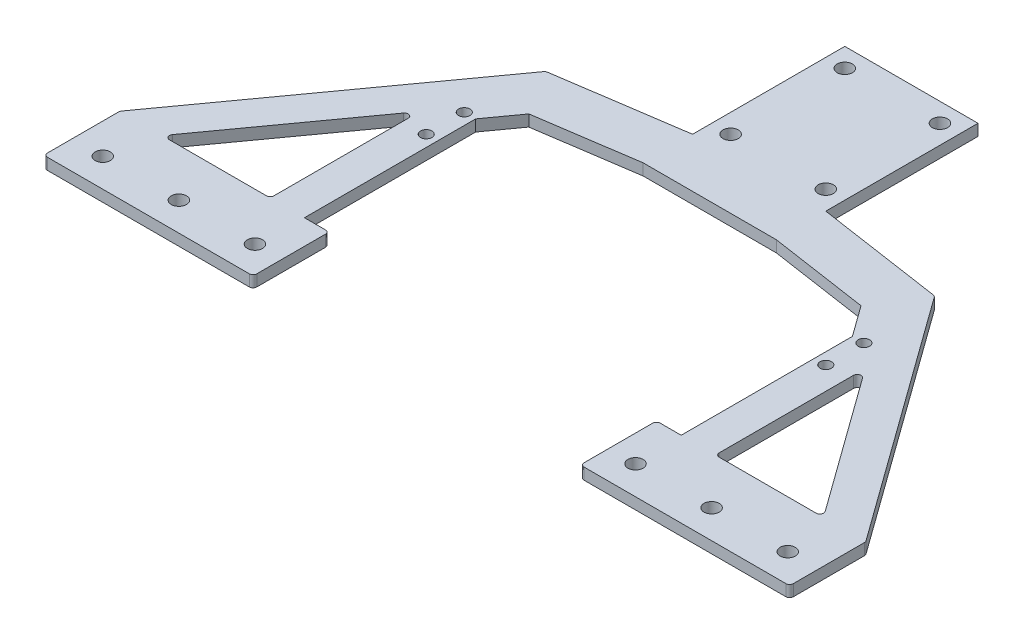
SolidWorks part; units mm, degrees
material "Thornel Mat VMA"
ref_plane "前视基准面" through (0, 0, 0) normal (0, 0, 1) x (1, 0, 0)
ref_plane "上视基准面" through (0, 0, 0) normal (0, 1, 0) x (1, 0, 0)
ref_plane "右视基准面" through (0, 0, 0) normal (1, 0, 0) x (0, 0, -1)
sketch "草图1" plane through (0, 0, 0) normal (0, 1, 0) x (1, 0, 0)
  line L0 (0, 0) -> (0, -110)
  line L1 (0, -110) -> (-62.5, -110)
  line L2 (-62.5, -110) -> (-62.5, -130)
  line L3 (-62.5, -130) -> (97.5, -130)
  line L4 (97.5, -130) -> (97.5, -110)
  line L5 (97.5, -110) -> (35, -110)
  line L6 (35, -110) -> (35, 0)
  line L7 (35, 0) -> (0, 0)
  line L9 (5, -5) -> (30, -5) construction
  line L10 (5, -5) -> (5, -35) construction
  line L11 (5, -35) -> (30, -35) construction
  line L12 (30, -5) -> (30, -35) construction
  circle A0 centre (5, -5) radius 2
  circle A1 centre (30, -5) radius 2
  circle A2 centre (5, -35) radius 2
  circle A3 centre (30, -35) radius 2
  circle A4 centre (-52.5, -122.5) radius 2
  circle A5 centre (-32.5, -122.5) radius 2
  circle A6 centre (-12.5, -122.5) radius 2
  circle A7 centre (7.5, -122.5) radius 2
  circle A8 centre (27.5, -122.5) radius 2
  circle A9 centre (47.5, -122.5) radius 2
  circle A10 centre (67.5, -122.5) radius 2
  circle A11 centre (87.5, -122.5) radius 2
  point P7 (17.5, -5)
  dimension "D10" = 4
  dimension "D11" = 7.5
  dimension "D13" = 4
  dimension "D1" = 35
  dimension "D2" = 130
  dimension "D3" = 20
  dimension "D4" = 160
  dimension "D5" = 62.5
  dimension "D6" = 5
  dimension "D7" = 5
  dimension "D8" = 5
  dimension "D9" = 30
  dimension "D12" = 10
  dimension "D15" = 10
  dimension "D14" = 8
extrude "凸台-拉伸1" add sketch "草图1" along normal blind 4
sketch "草图2" plane through (0, 4, 0) normal (0, 1, 0) x (1, 0, 0)
  line L0 (17.5, 0) -> (17.5, -130) construction
  line L1 (-35, -65) -> (70, -65) construction
  line L2 (-35, -65) -> (-35, -75) construction
  line L3 (-35, -75) -> (70, -75) construction
  line L5 (35, 0) -> (0, 0) construction
  line L6 (-62.5, -130) -> (97.5, -130) construction
  line L7 (70, -65) -> (70, -75) construction
  line L34 (0, 0) -> (0, -110) construction
  line L35 (0, -40) -> (0, -53)
  line L44 (0, -40) -> (-33.6, -45)
  line L45 (-33.6, -45) -> (-80.5, -110)
  line L46 (0, -53) -> (-26.1492, -56.8913)
  line L47 (-26.1492, -56.8913) -> (-32, -65)
  line L48 (-32, -65) -> (-32, -110)
  line L50 (-80.5, -110) -> (-80.5, -130)
  line L51 (-80.5, -130) -> (-62.5, -130)
  line L52 (-62.5, -130) -> (-62.5, -110)
  line L65 (0, -110) -> (-62.5, -110) construction
  line L66 (-32, -110) -> (-41, -110)
  line L67 (-69.4018, -110) -> (-41, -70.6372)
  line L68 (-41, -70.6372) -> (-41, -110)
  line L69 (-62.5, -110) -> (-69.4018, -110)
  line L71 (67, -65) -> (67, -110)
  line L72 (61.1492, -56.8913) -> (67, -65)
  line L73 (35, -53) -> (61.1492, -56.8913)
  line L74 (35, -40) -> (35, -53)
  line L75 (35, -40) -> (68.6, -45)
  line L76 (68.6, -45) -> (115.5, -110)
  line L77 (115.5, -110) -> (115.5, -130)
  line L78 (115.5, -130) -> (97.5, -130)
  line L79 (97.5, -130) -> (97.5, -110)
  line L80 (97.5, -110) -> (104.4018, -110)
  line L81 (104.4018, -110) -> (76, -70.6372)
  line L82 (76, -70.6372) -> (76, -110)
  line L83 (67, -110) -> (76, -110)
  line L84 (-52.5, -122.5) -> (-72.5, -122.5) construction
  circle A0 centre (-35, -65) radius 1.5
  circle A1 centre (-35, -75) radius 1.5
  circle A2 centre (70, -65) radius 1.5
  circle A3 centre (70, -75) radius 1.5
  circle A4 centre (-52.5, -122.5) radius 2 construction
  circle A5 centre (-72.5, -122.5) radius 2
  circle A6 centre (107.5, -122.5) radius 2
  dimension "D3" = 3
  dimension "D15" = 20
  dimension "D1" = 105
  dimension "D2" = 10
  dimension "D4" = 3
  dimension "D5" = 40
  dimension "D6" = 55
  dimension "D7" = 9
  dimension "D8" = 13
  dimension "D9" = 13
  dimension "D10" = 5
  dimension "D11" = 18
  dimension "D12" = 9
extrude "凸台-拉伸2" add sketch "草图2" against normal up to surface (4 mm away) up to face at (17.5, 0, 87.5)
sketch "草图3" plane through (0, 4, 0) normal (0, 1, 0) x (1, 0, 0)
  line L0 (0, -53) -> (35, -53)
  line L4 (35, -53) -> (35, -110)
  line L5 (35, -110) -> (60.5, -110)
  line L7 (60.5, -110) -> (60.5, -130)
  line L8 (-80.5, -130) -> (115.5, -130) construction
  line L9 (60.5, -130) -> (-25.5, -130)
  line L10 (-25.5, -130) -> (-25.5, -110)
  line L12 (-25.5, -110) -> (0, -110)
  line L13 (0, -110) -> (0, -53)
  line L15 (-80.5, -130) -> (115.5, -130) construction
  line L17 (0, -110) -> (-32, -110) construction
  line L18 (67, -110) -> (35, -110) construction
  circle A2 centre (-32.5, -122.5) radius 2 construction
  circle A3 centre (67.5, -122.5) radius 2 construction
  dimension "D1" = 7
  dimension "D2" = 7
extrude "切除-拉伸1" cut sketch "草图3" against normal through all
fillet "圆角2" radius 1 6 edges at (104.4018, 2, 110) (76, 2, 110) (76, 2, 70.6372) (-41, 2, 110) (-69.4018, 2, 110) (-41, 2, 70.6372)
fillet "圆角3" radius 1 10 edges at (115.5, 2, 130) (115.5, 2, 110) (68.6, 2, 45) (60.5, 2, 110) (60.5, 2, 130) (-25.5, 2, 130) (-25.5, 2, 110) (-33.6, 2, 45) (-80.5, 2, 110) (-80.5, 2, 130)
sketch "草图4" plane through (0, 4, 0) normal (0, 1, 0) x (1, 0, 0)
  line L22 (0, -40) -> (-33.1829, -44.9379)
  line L23 (-33.8467, -45.3419) -> (-80.3109, -109.738)
  line L24 (-80.5, -110.3231) -> (-80.5, -129)
  line L25 (-79.5, -130) -> (-26.5, -130)
  line L26 (-25.5, -129) -> (-25.5, -111)
  line L27 (-26.5, -110) -> (-32, -110)
  line L28 (-32, -110) -> (-32, -65)
  line L29 (-32, -65) -> (-26.1492, -56.8913)
  line L30 (-26.1492, -56.8913) -> (0, -53)
  line L31 (0, -53) -> (35, -53)
  line L32 (35, -53) -> (61.1492, -56.8913)
  line L33 (61.1492, -56.8913) -> (67, -65)
  line L34 (67, -65) -> (67, -110)
  line L35 (67, -110) -> (61.5, -110)
  line L36 (60.5, -111) -> (60.5, -129)
  line L37 (61.5, -130) -> (114.5, -130)
  line L38 (115.5, -129) -> (115.5, -110.3231)
  line L39 (115.3109, -109.738) -> (68.8467, -45.3419)
  line L40 (68.1829, -44.9379) -> (35, -40)
  line L41 (35, -40) -> (35, 0)
  line L42 (35, 0) -> (0, 0)
  line L43 (0, 0) -> (0, -40)
  line L44 (0, -40) -> (-33.1829, -44.9379)
  line L45 (-33.8467, -45.3419) -> (-80.3109, -109.738)
  line L46 (-80.5, -110.3231) -> (-80.5, -129)
  line L47 (-79.5, -130) -> (-26.5, -130)
  line L48 (-25.5, -129) -> (-25.5, -111)
  line L49 (-26.5, -110) -> (-32, -110)
  line L50 (-32, -110) -> (-32, -65)
  line L51 (-32, -65) -> (-26.1492, -56.8913)
  line L52 (-26.1492, -56.8913) -> (0, -53)
  line L53 (0, -53) -> (35, -53)
  line L54 (35, -53) -> (61.1492, -56.8913)
  line L55 (61.1492, -56.8913) -> (67, -65)
  line L56 (67, -65) -> (67, -110)
  line L57 (67, -110) -> (61.5, -110)
  line L58 (60.5, -111) -> (60.5, -129)
  line L59 (61.5, -130) -> (114.5, -130)
  line L60 (115.5, -129) -> (115.5, -110.3231)
  line L61 (115.3109, -109.738) -> (68.8467, -45.3419)
  line L62 (68.1829, -44.9379) -> (35, -40)
  line L63 (35, -40) -> (35, 0)
  line L64 (35, 0) -> (0, 0)
  line L65 (0, 0) -> (0, -40)
  arc A10 (-33.1829, -44.9379) -> (-33.8467, -45.3419) centre (-33.0357, -45.927) ccw
  arc A11 (-80.3109, -109.738) -> (-80.5, -110.3231) centre (-79.5, -110.3231) ccw
  arc A12 (-80.5, -129) -> (-79.5, -130) centre (-79.5, -129) ccw
  arc A13 (-26.5, -130) -> (-25.5, -129) centre (-26.5, -129) ccw
  arc A14 (-25.5, -111) -> (-26.5, -110) centre (-26.5, -111) ccw
  arc A15 (61.5, -110) -> (60.5, -111) centre (61.5, -111) ccw
  arc A16 (60.5, -129) -> (61.5, -130) centre (61.5, -129) ccw
  arc A17 (114.5, -130) -> (115.5, -129) centre (114.5, -129) ccw
  arc A18 (115.5, -110.3231) -> (115.3109, -109.738) centre (114.5, -110.3231) ccw
  arc A19 (68.8467, -45.3419) -> (68.1829, -44.9379) centre (68.0357, -45.927) ccw
  arc A20 (-33.1829, -44.9379) -> (-33.8467, -45.3419) centre (-33.0357, -45.927) ccw
  arc A21 (-80.3109, -109.738) -> (-80.5, -110.3231) centre (-79.5, -110.3231) ccw
  arc A22 (-80.5, -129) -> (-79.5, -130) centre (-79.5, -129) ccw
  arc A23 (-26.5, -130) -> (-25.5, -129) centre (-26.5, -129) ccw
  arc A24 (-25.5, -111) -> (-26.5, -110) centre (-26.5, -111) ccw
  arc A25 (61.5, -110) -> (60.5, -111) centre (61.5, -111) ccw
  arc A26 (60.5, -129) -> (61.5, -130) centre (61.5, -129) ccw
  arc A27 (114.5, -130) -> (115.5, -129) centre (114.5, -129) ccw
  arc A28 (115.5, -110.3231) -> (115.3109, -109.738) centre (114.5, -110.3231) ccw
  arc A29 (68.8467, -45.3419) -> (68.1829, -44.9379) centre (68.0357, -45.927) ccw
  dimension "D1" = 0
extrude "切除-拉伸2" cut sketch "草图4" against normal blind 11 from offset 1.7 offset against normal yes
sketch "草图5" plane through (0, 4, 0) normal (0, 1, 0) x (1, 0, 0)
  line L0 (102.4471, -110) -> (77, -110) construction
  line L1 (77.8109, -73.147) -> (103.2581, -108.4149) construction
  line L2 (76, -109) -> (76, -73.7322) construction
  line L3 (-41, -73.7322) -> (-41, -109) construction
  line L4 (-42, -110) -> (-67.4471, -110) construction
  line L5 (-68.2581, -108.4149) -> (-42.8109, -73.147) construction
  line L6 (102.4471, -110) -> (77, -110)
  line L7 (77.8109, -73.147) -> (103.2581, -108.4149)
  line L8 (76, -109) -> (76, -73.7322)
  line L9 (-41, -73.7322) -> (-41, -109)
  line L10 (-42, -110) -> (-67.4471, -110)
  line L11 (-68.2581, -108.4149) -> (-42.8109, -73.147)
  line L22 (0, -40) -> (-33.1829, -44.9379)
  line L23 (-33.8467, -45.3419) -> (-80.3109, -109.738)
  line L24 (-80.5, -110.3231) -> (-80.5, -129)
  line L25 (-79.5, -130) -> (-26.5, -130)
  line L26 (-25.5, -129) -> (-25.5, -111)
  line L27 (-26.5, -110) -> (-32, -110)
  line L28 (-32, -110) -> (-32, -65)
  line L29 (-32, -65) -> (-26.1492, -56.8913)
  line L30 (-26.1492, -56.8913) -> (0, -53)
  line L31 (0, -53) -> (35, -53)
  line L32 (35, -53) -> (61.1492, -56.8913)
  line L33 (61.1492, -56.8913) -> (67, -65)
  line L34 (67, -65) -> (67, -110)
  line L35 (67, -110) -> (61.5, -110)
  line L36 (60.5, -111) -> (60.5, -129)
  line L37 (61.5, -130) -> (114.5, -130)
  line L38 (115.5, -129) -> (115.5, -110.3231)
  line L39 (115.3109, -109.738) -> (68.8467, -45.3419)
  line L40 (68.1829, -44.9379) -> (35, -40)
  line L41 (35, -40) -> (35, 0)
  line L42 (35, 0) -> (0, 0)
  line L43 (0, 0) -> (0, -40)
  line L44 (0, -40) -> (-33.1829, -44.9379)
  line L45 (-33.8467, -45.3419) -> (-80.3109, -109.738)
  line L46 (-80.5, -110.3231) -> (-80.5, -129)
  line L47 (-79.5, -130) -> (-26.5, -130)
  line L48 (-25.5, -129) -> (-25.5, -111)
  line L49 (-26.5, -110) -> (-32, -110)
  line L50 (-32, -110) -> (-32, -65)
  line L51 (-32, -65) -> (-26.1492, -56.8913)
  line L52 (-26.1492, -56.8913) -> (0, -53)
  line L53 (0, -53) -> (35, -53)
  line L54 (35, -53) -> (61.1492, -56.8913)
  line L55 (61.1492, -56.8913) -> (67, -65)
  line L56 (67, -65) -> (67, -110)
  line L57 (67, -110) -> (61.5, -110)
  line L58 (60.5, -111) -> (60.5, -129)
  line L59 (61.5, -130) -> (114.5, -130)
  line L60 (115.5, -129) -> (115.5, -110.3231)
  line L61 (115.3109, -109.738) -> (68.8467, -45.3419)
  line L62 (68.1829, -44.9379) -> (35, -40)
  line L63 (35, -40) -> (35, 0)
  line L64 (35, 0) -> (0, 0)
  line L65 (0, 0) -> (0, -40)
  arc A0 (102.4471, -110) -> (103.2581, -108.4149) centre (102.4471, -109) ccw construction
  circle A1 centre (30, -5) radius 2
  circle A2 centre (30, -5) radius 2
  circle A3 centre (30, -35) radius 2
  circle A4 centre (30, -35) radius 2
  circle A5 centre (-32.5, -122.5) radius 2
  circle A6 centre (-32.5, -122.5) radius 2
  circle A7 centre (87.5, -122.5) radius 2
  circle A8 centre (87.5, -122.5) radius 2
  circle A9 centre (-72.5, -122.5) radius 2
  circle A10 centre (-72.5, -122.5) radius 2
  circle A11 centre (-35, -65) radius 1.5
  circle A12 centre (-35, -65) radius 1.5
  circle A13 centre (-35, -75) radius 1.5
  circle A14 centre (-35, -75) radius 1.5
  circle A15 centre (107.5, -122.5) radius 2
  circle A16 centre (107.5, -122.5) radius 2
  circle A17 centre (70, -75) radius 1.5
  circle A18 centre (70, -75) radius 1.5
  circle A19 centre (70, -65) radius 1.5
  circle A20 centre (70, -65) radius 1.5
  circle A21 centre (67.5, -122.5) radius 2
  circle A22 centre (67.5, -122.5) radius 2
  circle A23 centre (-52.5, -122.5) radius 2
  circle A24 centre (-52.5, -122.5) radius 2
  circle A25 centre (5, -35) radius 2
  circle A26 centre (5, -35) radius 2
  circle A27 centre (5, -5) radius 2
  circle A28 centre (5, -5) radius 2
  arc A29 (76, -109) -> (77, -110) centre (77, -109) ccw construction
  arc A30 (77.8109, -73.147) -> (76, -73.7322) centre (77, -73.7322) ccw construction
  arc A31 (-41, -73.7322) -> (-42.8109, -73.147) centre (-42, -73.7322) ccw construction
  arc A32 (-42, -110) -> (-41, -109) centre (-42, -109) ccw construction
  arc A33 (-68.2581, -108.4149) -> (-67.4471, -110) centre (-67.4471, -109) ccw construction
  arc A34 (102.4471, -110) -> (103.2581, -108.4149) centre (102.4471, -109) ccw
  arc A35 (76, -109) -> (77, -110) centre (77, -109) ccw
  arc A36 (77.8109, -73.147) -> (76, -73.7322) centre (77, -73.7322) ccw
  arc A37 (-41, -73.7322) -> (-42.8109, -73.147) centre (-42, -73.7322) ccw
  arc A38 (-33.1829, -44.9379) -> (-33.8467, -45.3419) centre (-33.0357, -45.927) ccw
  arc A39 (-80.3109, -109.738) -> (-80.5, -110.3231) centre (-79.5, -110.3231) ccw
  arc A40 (-80.5, -129) -> (-79.5, -130) centre (-79.5, -129) ccw
  arc A41 (-26.5, -130) -> (-25.5, -129) centre (-26.5, -129) ccw
  arc A42 (-25.5, -111) -> (-26.5, -110) centre (-26.5, -111) ccw
  arc A43 (61.5, -110) -> (60.5, -111) centre (61.5, -111) ccw
  arc A44 (60.5, -129) -> (61.5, -130) centre (61.5, -129) ccw
  arc A45 (114.5, -130) -> (115.5, -129) centre (114.5, -129) ccw
  arc A46 (115.5, -110.3231) -> (115.3109, -109.738) centre (114.5, -110.3231) ccw
  arc A47 (68.8467, -45.3419) -> (68.1829, -44.9379) centre (68.0357, -45.927) ccw
  arc A48 (-33.1829, -44.9379) -> (-33.8467, -45.3419) centre (-33.0357, -45.927) ccw
  arc A49 (-80.3109, -109.738) -> (-80.5, -110.3231) centre (-79.5, -110.3231) ccw
  arc A50 (-80.5, -129) -> (-79.5, -130) centre (-79.5, -129) ccw
  arc A51 (-26.5, -130) -> (-25.5, -129) centre (-26.5, -129) ccw
  arc A52 (-25.5, -111) -> (-26.5, -110) centre (-26.5, -111) ccw
  arc A53 (61.5, -110) -> (60.5, -111) centre (61.5, -111) ccw
  arc A54 (60.5, -129) -> (61.5, -130) centre (61.5, -129) ccw
  arc A55 (114.5, -130) -> (115.5, -129) centre (114.5, -129) ccw
  arc A56 (115.5, -110.3231) -> (115.3109, -109.738) centre (114.5, -110.3231) ccw
  arc A57 (68.8467, -45.3419) -> (68.1829, -44.9379) centre (68.0357, -45.927) ccw
  arc A58 (-42, -110) -> (-41, -109) centre (-42, -109) ccw
  arc A59 (-68.2581, -108.4149) -> (-67.4471, -110) centre (-67.4471, -109) ccw
  dimension "D1" = 0
  dimension "D2" = 0
  dimension "D3" = 0
  dimension "D4" = 0
  dimension "D5" = 0
  dimension "D6" = 0
  dimension "D7" = 0
  dimension "D8" = 0
  dimension "D9" = 0
  dimension "D10" = 0
  dimension "D11" = 0
  dimension "D12" = 0
  dimension "D13" = 0
  dimension "D14" = 0
  dimension "D15" = 0
extrude "凸台-拉伸3" add sketch "草图5" along normal blind 1.3
